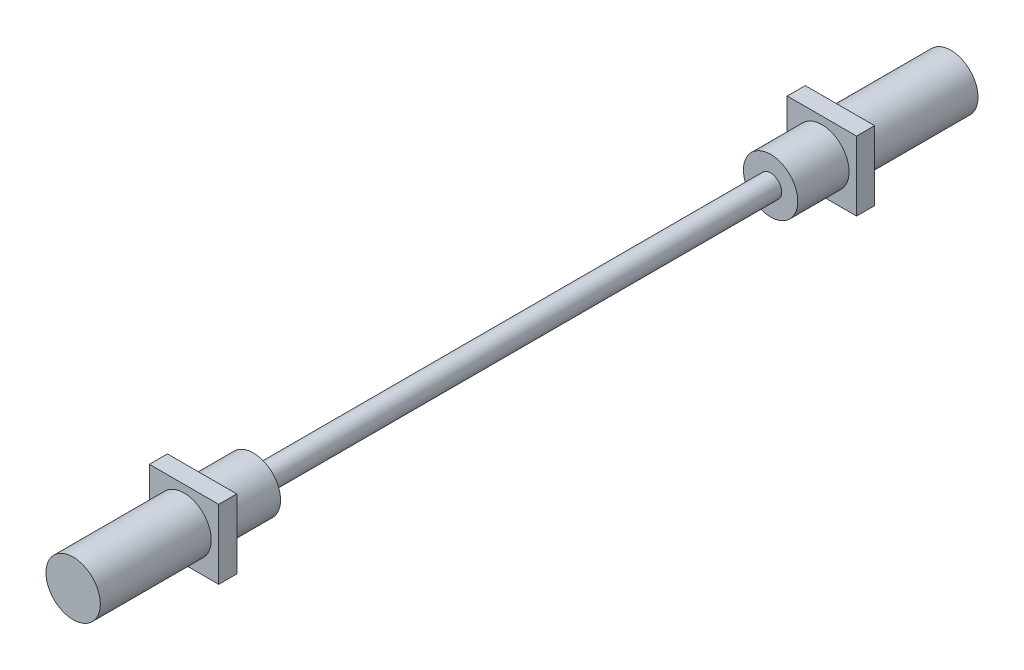
SolidWorks part; units mm, degrees
ref_plane "Front Plane" through (0, 0, 0) normal (0, 0, 1) x (1, 0, 0)
ref_plane "Top Plane" through (0, 0, 0) normal (0, 1, 0) x (1, 0, 0)
ref_plane "Right Plane" through (0, 0, 0) normal (1, 0, 0) x (0, 0, -1)
sketch "Sketch1" plane through (0, 0, 0) normal (0, 0, 1) x (1, 0, 0)
  circle A0 centre (0, 0) radius 1.016
  dimension "D1" = 2.032
extrude "Boss-Extrude1" add sketch "Sketch1" along normal blind 47.371
ref_plane "Plane1" through (0, 0, 47.371) normal (0, 0, 1) x (1, 0, 0)
ref_plane "Plane2" through (0, 0, 0) normal (0, 0, -1) x (-1, 0, 0)
sketch "Sketch2" plane through (0, 0, 0) normal (0, 0, -1) x (-1, 0, 0)
  circle A0 centre (0, 0) radius 2.4892
  dimension "D1" = 4.9784
extrude "Boss-Extrude2" add sketch "Sketch2" along normal blind 4.699
ref_plane "Plane3" through (0, 0, -4.699) normal (0, 0, -1) x (-1, 0, 0)
sketch "Sketch3" plane through (0, 0, -4.699) normal (0, 0, -1) x (-1, 0, 0)
  line L1 (-3.175, 3.175) -> (3.175, 3.175)
  line L2 (-3.175, 3.175) -> (-3.175, -3.175)
  line L3 (-3.175, -3.175) -> (3.175, -3.175)
  line L4 (3.175, 3.175) -> (3.175, -3.175)
  line L5 (-3.175, 3.175) -> (3.175, -3.175) construction
  line L6 (-3.175, -3.175) -> (3.175, 3.175) construction
  point P0 (0, 0)
  dimension "D1" = 6.35
  dimension "D2" = 6.35
extrude "Boss-Extrude3" add sketch "Sketch3" along normal blind 1.651
ref_plane "Plane4" through (0, 0, -6.35) normal (0, 0, -1) x (-1, 0, 0)
sketch "Sketch4" plane through (0, 0, -6.35) normal (0, 0, -1) x (-1, 0, 0)
  circle A0 centre (0, 0) radius 2.4892
  dimension "D1" = 4.9784
extrude "Boss-Extrude4" add sketch "Sketch4" along normal blind 10.16
sketch "Sketch5" plane through (0, 0, 47.371) normal (0, 0, 1) x (1, 0, 0)
  circle A0 centre (0, 0) radius 2.4892
  dimension "D1" = 4.9784
extrude "Boss-Extrude5" add sketch "Sketch5" along normal blind 4.699
ref_plane "Plane5" through (0, 0, 52.07) normal (0, 0, 1) x (1, 0, 0)
sketch "Sketch6" plane through (0, 0, 52.07) normal (0, 0, 1) x (1, 0, 0)
  line L1 (-3.175, 3.175) -> (3.175, 3.175)
  line L2 (-3.175, 3.175) -> (-3.175, -3.175)
  line L3 (-3.175, -3.175) -> (3.175, -3.175)
  line L4 (3.175, 3.175) -> (3.175, -3.175)
  line L5 (-3.175, 3.175) -> (3.175, -3.175) construction
  line L6 (-3.175, -3.175) -> (3.175, 3.175) construction
  point P0 (0, 0)
  dimension "D1" = 6.35
  dimension "D2" = 6.35
extrude "Boss-Extrude6" add sketch "Sketch6" along normal blind 1.651
ref_plane "Plane6" through (0, 0, 53.721) normal (0, 0, 1) x (1, 0, 0)
sketch "Sketch7" plane through (0, 0, 53.721) normal (0, 0, 1) x (1, 0, 0)
  circle A0 centre (0, 0) radius 2.4892
  dimension "D1" = 4.9784
extrude "Boss-Extrude7" add sketch "Sketch7" along normal blind 10.16
ref_plane "center plane" through (0, 0, 23.6855) normal (0, 0, -1) x (-1, 0, 0)
